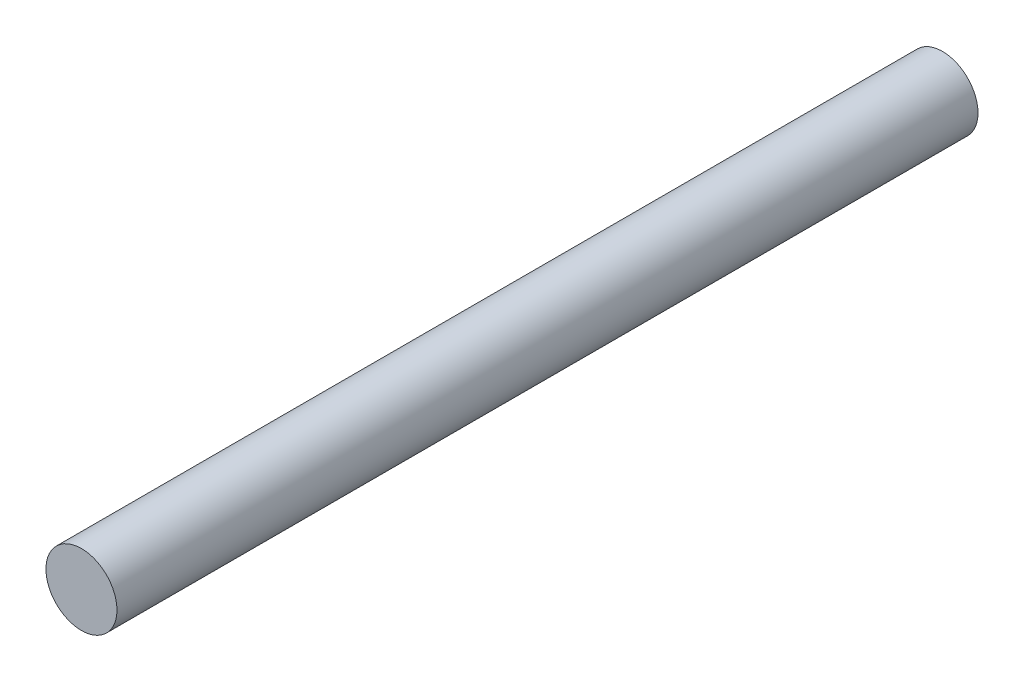
SolidWorks part; units mm, degrees
ref_plane "Front Plane" through (0, 0, 0) normal (0, 0, 1) x (1, 0, 0)
ref_plane "Top Plane" through (0, 0, 0) normal (0, 1, 0) x (1, 0, 0)
ref_plane "Right Plane" through (0, 0, 0) normal (1, 0, 0) x (0, 0, -1)
sketch "Sketch1" plane through (0, 0, 0) normal (0, 0, 1) x (1, 0, 0)
  circle A0 centre (0, 0) radius 4.191
extrude "Extrude1" add sketch "Sketch1" along normal blind 101.6
